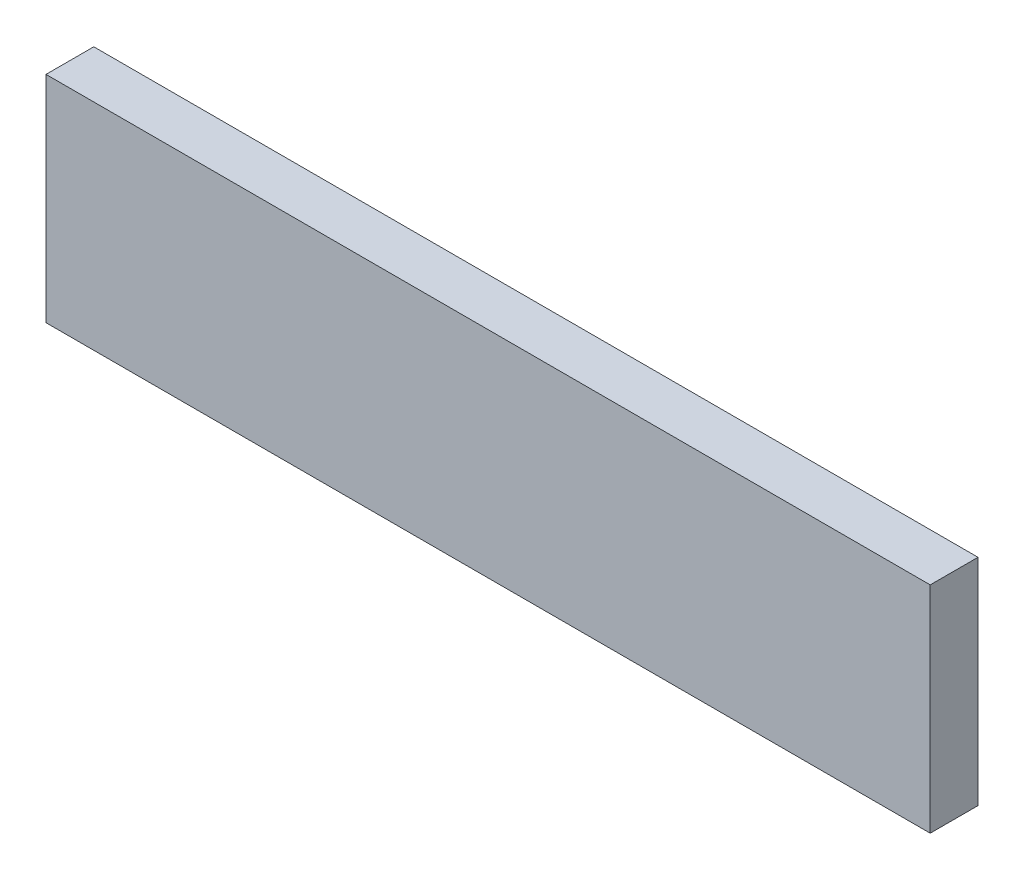
SolidWorks part; units mm, degrees
ref_plane "Plano frontal" through (0, 0, 0) normal (0, 0, 1) x (1, 0, 0)
ref_plane "Plano superior" through (0, 0, 0) normal (0, 1, 0) x (1, 0, 0)
ref_plane "Plano direito" through (0, 0, 0) normal (1, 0, 0) x (0, 0, -1)
other "Centro da massa"
sketch "Esboço2" plane through (0, 0, 0) normal (0, 0, 1) x (1, 0, 0)
  line L1 (92.5, -22.5) -> (-92.5, -22.5)
  line L2 (92.5, -22.5) -> (92.5, 22.5)
  line L3 (92.5, 22.5) -> (-92.5, 22.5)
  line L4 (-92.5, -22.5) -> (-92.5, 22.5)
  line L5 (92.5, -22.5) -> (-92.5, 22.5) construction
  line L6 (92.5, 22.5) -> (-92.5, -22.5) construction
  point P0 (0, 0)
  dimension "D1" = 185
  dimension "D2" = 45
extrude "Ressalto-extrusão1" add sketch "Esboço2" along normal blind 10
